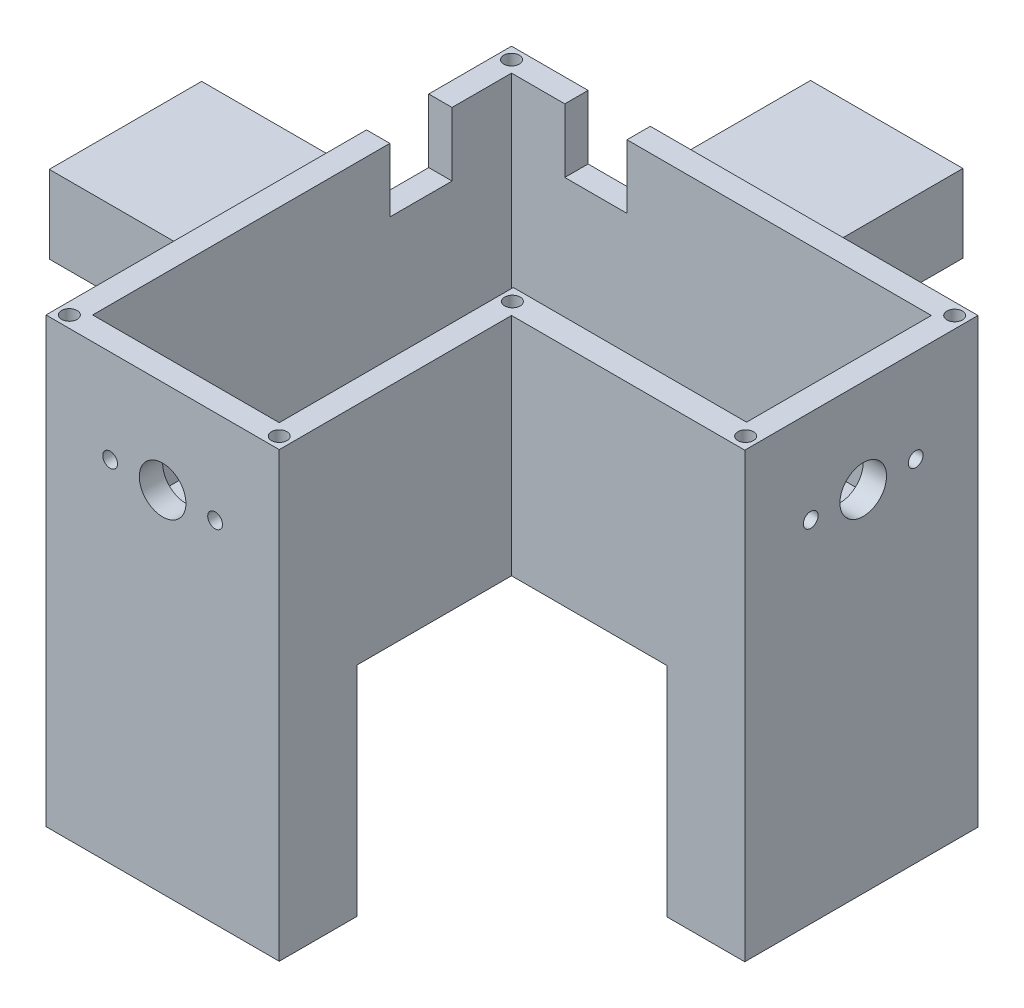
SolidWorks part; units mm, degrees
other "Marquage1"
sketch "Esquisse65" plane through (-83.92, 29, -58.86) normal (-0.3844, 0.8969, -0.2184) x (-0.4847, 0.0053, 0.8747)
ref_plane "Plan de face" through (0, 0, 0) normal (0, 0, 1) x (1, 0, 0)
ref_plane "Plan de dessus" through (0, 0, 0) normal (0, 1, 0) x (1, 0, 0)
ref_plane "Plan de droite" through (0, 0, 0) normal (1, 0, 0) x (0, 0, -1)
sketch "Esquisse1" plane through (0, 0, 0) normal (0, 1, 0) x (1, 0, 0)
  line L1 (0, 0) -> (-83.92, 0)
  line L2 (0, 0) -> (0, 19.6)
  line L3 (0, 19.6) -> (-83.92, 19.6)
  line L4 (-83.92, 0) -> (-83.92, 19.6)
  line L5 (-44.86, -24.34) -> (-25.26, -24.34)
  line L6 (-44.86, -24.34) -> (-44.86, 58.86)
  line L7 (-44.86, 58.86) -> (-25.26, 58.86)
  line L8 (-25.26, -24.34) -> (-25.26, 58.86)
  line L9 (-47.86, 22.6) -> (3, 22.6)
  line L10 (-47.86, 22.6) -> (-47.86, -27.34)
  line L11 (-47.86, -27.34) -> (3, -27.34)
  line L12 (3, 22.6) -> (3, -27.34)
  line L13 (3, -27.34) -> (-22.26, -27.34)
  line L14 (3, -27.34) -> (3, -3)
  line L15 (3, -3) -> (-22.26, -3)
  line L16 (-22.26, -27.34) -> (-22.26, -3)
  dimension "D1" = 83.92
  dimension "D2" = 19.6
  dimension "D3" = 19.6
  dimension "D4" = 83.2
  dimension "D5" = 39.26
  dimension "D6" = 3
  dimension "D7" = 3
  dimension "D8" = 25.26
  dimension "D9" = 3
  dimension "D10" = 3
  dimension "D11" = 3
  dimension "D12" = 3
extrude "Boss.-Extru.1" add sketch "Esquisse1" along normal blind 29.8 contours L10 L3 L4 L1 | L3 L10 L1 L6 | L9 L10 L3 L6 | L9 L6 L3 L8 | L11 L16 L15 L12 L9 L8 L3 L2 L1 L5 L6 L10 | L1 L8 L3 L6 | L5 L8 L1 L6 | L8 L1 L2 L3 | L6 L9 L8 L7
sketch "Esquisse2" plane through (0, 29.8, 0) normal (0, 1, 0) x (1, 0, 0)
  line L0 (-25.26, 22.6) -> (3, 22.6) construction
  line L1 (-44.86, 19.6) -> (-25.26, 19.6)
  line L2 (-44.86, 19.6) -> (-44.86, -24.34)
  line L3 (-44.86, -24.34) -> (-25.26, -24.34)
  line L4 (-25.26, 19.6) -> (-25.26, -24.34)
  line L5 (-25.26, 19.6) -> (0, 19.6)
  line L6 (-25.26, 19.6) -> (-25.26, 0)
  line L7 (-25.26, 0) -> (0, 0)
  line L8 (0, 19.6) -> (0, 0)
  line L11 (-47.86, -27.34) -> (-22.26, -27.34) construction
  line L12 (-22.26, -27.34) -> (-22.26, -3) construction
  line L13 (-47.86, 0) -> (-47.86, -27.34) construction
  dimension "D1" = 3
  dimension "D2" = 3
  dimension "D3" = 3
  dimension "D4" = 3
extrude "Enlèv. mat.-Extru.1" cut sketch "Esquisse2" against normal blind 24.8 contours L4 L1 L2 L3 | L8 L5 L4 L7
sketch "Esquisse3" plane through (0, 29.8, 0) normal (0, 1, 0) x (1, 0, 0)
  line L1 (-83.92, 19.6) -> (-47.86, 19.6)
  line L2 (-83.92, 19.6) -> (-83.92, 0)
  line L3 (-83.92, 0) -> (-47.86, 0)
  line L4 (-47.86, 19.6) -> (-47.86, 0)
  line L5 (-44.86, 58.86) -> (-25.26, 58.86)
  line L6 (-44.86, 58.86) -> (-44.86, 22.6)
  line L7 (-44.86, 22.6) -> (-25.26, 22.6)
  line L8 (-25.26, 58.86) -> (-25.26, 22.6)
extrude "Enlèv. mat.-Extru.2" cut sketch "Esquisse3" against normal blind 19.8
ref_plane "Plan1" through (-47.86, 29.8, 27.34) normal (0, -1, 0) x (-1, 0, 0)
sketch "Esquisse6" plane through (-47.86, 29.8, 27.34) normal (0, -1, 0) x (1, 0, 0)
  line L1 (0, -49.94) -> (56.5877, -49.94)
  line L2 (0, -49.94) -> (0, 5.1698)
  line L3 (0, 5.1698) -> (56.5877, 5.1698)
  line L4 (56.5877, -49.94) -> (56.5877, 5.1698)
extrude "Enlèv. mat.-Extru.5" cut sketch "Esquisse6" along normal blind 5
sketch "Esquisse7" plane through (-47.86, 0, 0) normal (-1, 0, 0) x (0, 0, 1)
  line L0 (-9.8, 10) -> (-9.8, 24.8)
  line L1 (0, 10) -> (-19.6, 10) construction
  line L2 (27.34, 24.8) -> (-22.6, 24.8) construction
  line L4 (-9.8, 24.8) -> (-13.8, 24.8)
  line L5 (-9.8, 24.8) -> (-9.8, 20.8)
  line L6 (-9.8, 20.8) -> (-13.8, 20.8)
  line L7 (-13.8, 24.8) -> (-13.8, 20.8)
  line L8 (-9.8, 20.8) -> (-5.8, 20.8)
  line L9 (-9.8, 20.8) -> (-9.8, 24.8)
  line L10 (-9.8, 24.8) -> (-5.8, 24.8)
  line L11 (-5.8, 20.8) -> (-5.8, 24.8)
  line M5 (27.34, 24.8) -> (-22.6, 24.8)
  dimension "D1" = 4
  dimension "D2" = 4
  dimension "D3" = 4
extrude "Enlèv. mat.-Extru.6" cut sketch "Esquisse7" against normal blind 5 contours L7 L6 L0 M5 | L8 L11 L0 M5
sketch "Esquisse8" plane through (0, 0, -22.6) normal (0, 0, -1) x (-1, 0, 0)
  line L0 (35.06, 10) -> (35.06, 24.8)
  line L1 (44.86, 10) -> (25.26, 10) construction
  line L2 (47.86, 24.8) -> (-3, 24.8) construction
  line L4 (35.06, 24.8) -> (31.06, 24.8)
  line L5 (35.06, 24.8) -> (35.06, 20.8)
  line L6 (35.06, 20.8) -> (31.06, 20.8)
  line L7 (31.06, 24.8) -> (31.06, 20.8)
  line L8 (35.06, 24.8) -> (39.06, 24.8)
  line L9 (35.06, 24.8) -> (35.06, 20.8)
  line L10 (35.06, 20.8) -> (39.06, 20.8)
  line L11 (39.06, 24.8) -> (39.06, 20.8)
  line M5 (47.86, 24.8) -> (-3, 24.8)
  dimension "D1" = 4
  dimension "D2" = 4
  dimension "D3" = 4
extrude "Enlèv. mat.-Extru.7" cut sketch "Esquisse8" against normal blind 5 contours L11 L0 L10 M5 | L7 L6 L0 M5
sketch "Esquisse10" plane through (-83.92, 0, 0) normal (-1, 0, 0) x (0, 0, 1)
  line L0 (-9.8, 0) -> (-9.8, 10)
  line L1 (0, 0) -> (-19.6, 0) construction
  line L2 (-19.6, 10) -> (0, 10) construction
  line L3 (-9.8, 10) -> (-19.6, 0)
  line L4 (-9.8, 10) -> (0, 0)
  circle A0 centre (-14.7, 5) radius 1.5
  circle A1 centre (-4.9, 5) radius 1.5
extrude "Enlèv. mat.-Extru.9" cut sketch "Esquisse10" against normal blind 5 contours L4 A1 | L4 A1 | L3 A0 | L3 A0
sketch "Esquisse11" plane through (0, 0, -58.86) normal (0, 0, -1) x (-1, 0, 0)
  line L0 (35.06, 0) -> (35.06, 10)
  line L1 (44.86, 0) -> (25.26, 0) construction
  line L2 (25.26, 10) -> (44.86, 10) construction
  line L3 (25.26, 10) -> (35.06, 0)
  line L4 (44.86, 10) -> (35.06, 0)
  circle A0 centre (30.16, 5) radius 1.5
  circle A1 centre (39.96, 5) radius 1.5
extrude "Enlèv. mat.-Extru.10" cut sketch "Esquisse11" against normal blind 5 contours L3 A0 | L3 A0 | L4 A1 | L4 A1
sketch "Esquisse20" plane through (0, 0, 0) normal (0, -1, 0) x (1, 0, 0)
  line L0 (-22.26, 27.34) -> (-22.26, 3) construction
  line L1 (-47.86, 27.34) -> (-22.26, 27.34)
  line L2 (-47.86, 27.34) -> (-47.86, 17.34)
  line L3 (-47.86, 17.34) -> (-22.26, 17.34)
  line L4 (-22.26, 27.34) -> (-22.26, 17.34)
extrude "Boss.-Extru.4" add sketch "Esquisse20" along normal blind 30.13
sketch "Esquisse21" plane through (0, 0, 0) normal (0, -1, 0) x (1, 0, 0)
  line L0 (-25.26, -22.6) -> (3, -22.6) construction
  line L1 (3, 3) -> (-7, 3)
  line L2 (3, 3) -> (3, -22.6)
  line L3 (3, -22.6) -> (-7, -22.6)
  line L4 (-7, 3) -> (-7, -22.6)
  dimension "D1" = 10
extrude "Boss.-Extru.5" add sketch "Esquisse21" along normal blind 30.13
sketch "Esquisse22" plane through (0, -30.13, 0) normal (0, -1, 0) x (1, 0, 0)
  line L0 (-35.06, 17.34) -> (-35.06, 27.34)
  line L1 (-47.86, 17.34) -> (-22.26, 17.34) construction
  line L2 (-22.26, 27.34) -> (-47.86, 27.34) construction
  line L3 (-35.06, 27.34) -> (-47.86, 17.34)
  line L4 (-35.06, 27.34) -> (-22.26, 17.34)
  line L5 (-7, -9.8) -> (3, -9.8)
  line L6 (-7, 3) -> (-7, -22.6) construction
  line L7 (3, -22.6) -> (3, 3) construction
  line L8 (3, -9.8) -> (-7, -22.6)
  line L9 (3, -9.8) -> (-7, 3)
  circle A0 centre (-28.66, 22.34) radius 1.5
  circle A1 centre (-41.46, 22.34) radius 1.5
  circle A2 centre (-2, -16.2) radius 1.5
  circle A3 centre (-2, -3.4) radius 1.5
extrude "Enlèv. mat.-Extru.17" cut sketch "Esquisse22" against normal blind 5 contours L9 A3 | L4 A0 | L4 A0 | L3 A1 | L3 A1 | A2
sketch "Esquisse23" plane through (0, 0, -22.6) normal (0, 0, -1) x (-1, 0, 0)
  line L0 (44.86, 10) -> (25.26, 10) construction
  line L1 (-3, 24.8) -> (7, 24.8)
  line L2 (-3, 24.8) -> (-3, -30.13)
  line L3 (-3, -30.13) -> (7, -30.13)
  line L4 (7, 24.8) -> (7, -30.13)
  line L5 (25.26, 0) -> (7, 0)
  line L6 (25.26, 0) -> (25.26, 24.8)
  line L7 (25.26, 24.8) -> (7, 24.8)
  line L8 (7, 0) -> (7, 24.8)
  line L9 (47.86, 0) -> (44.86, 0)
  line L10 (47.86, 0) -> (47.86, 10)
  line L11 (47.86, 10) -> (44.86, 10)
  line L12 (44.86, 0) -> (44.86, 10)
  line L13 (47.86, 24.8) -> (39.06, 24.8)
  line L14 (47.86, 24.8) -> (47.86, 10)
  line L15 (47.86, 10) -> (39.06, 10)
  line L16 (39.06, 24.8) -> (39.06, 10)
  line L18 (39.06, 10) -> (31.06, 10)
  line L19 (39.06, 10) -> (39.06, 20.8)
  line L20 (39.06, 20.8) -> (31.06, 20.8)
  line L21 (31.06, 10) -> (31.06, 20.8)
  line L22 (31.06, 24.8) -> (25.26, 24.8)
  line L23 (31.06, 24.8) -> (31.06, 10)
  line L24 (31.06, 10) -> (25.26, 10)
  line L25 (25.26, 24.8) -> (25.26, 10)
  line M26 (47.86, 24.8) -> (39.06, 24.8)
  line M27 (39.06, 24.8) -> (39.06, 20.8)
  line M28 (39.06, 20.8) -> (31.06, 20.8)
  line M29 (31.06, 20.8) -> (31.06, 24.8)
  line M30 (31.06, 24.8) -> (-3, 24.8)
  line M31 (-3, 24.8) -> (-3, -30.13)
  line M32 (-3, -30.13) -> (7, -30.13)
  line M33 (7, -30.13) -> (7, 0)
  line M34 (7, 0) -> (25.26, 0)
  line M35 (25.26, 0) -> (25.26, 10)
  line M36 (25.26, 10) -> (44.86, 10)
  line M39 (47.86, 0) -> (47.86, 24.8)
extrude "Boss.-Extru.9" add sketch "Esquisse23" along normal blind 2.2 contours L16 L11 M27 M36 M39 M26 | L21 L16 M36 M28 | L6 L4 M35 M30 M34 | L21 L6 M36 M29 M30 | L4 M30 M31 M32 M33
sketch "Esquisse28" plane through (0, 0, 3) normal (0, 0, 1) x (1, 0, 0)
  line L0 (3, 24.8) -> (3, -30.13) construction
  line L1 (-22.26, 24.8) -> (3, 24.8)
  line L2 (-22.26, 24.8) -> (-22.26, 0)
  line L3 (-22.26, 0) -> (3, 0)
  line L4 (3, 24.8) -> (3, 0)
  line L6 (3, 0) -> (-7, 0)
  line L7 (3, 0) -> (3, -30.13)
  line L8 (3, -30.13) -> (-7, -30.13)
  line L9 (-7, 0) -> (-7, -30.13)
  line M1 (3, -30.13) -> (3, 24.8)
  line M2 (3, 24.8) -> (-22.26, 24.8)
  line M3 (-22.26, 24.8) -> (-22.26, 0)
  line M4 (-22.26, 0) -> (-7, 0)
  line M5 (-7, 0) -> (-7, -30.13)
  line M6 (-7, -30.13) -> (3, -30.13)
extrude "Boss.-Extru.10" add sketch "Esquisse28" along normal blind 2.2 contours L3 M4 M1 M2 M3 | L3 M5 M6 M1
sketch "Esquisse29" plane through (-22.26, 0, 0) normal (1, 0, 0) x (0, 0, -1)
  line L1 (-27.34, 24.8) -> (-5.2, 24.8)
  line L2 (-27.34, 24.8) -> (-27.34, 0)
  line L3 (-27.34, 0) -> (-5.2, 0)
  line L4 (-5.2, 24.8) -> (-5.2, 0)
  line L5 (-17.34, 0) -> (-27.34, 0)
  line L6 (-17.34, 0) -> (-17.34, -30.13)
  line L7 (-17.34, -30.13) -> (-27.34, -30.13)
  line L8 (-27.34, 0) -> (-27.34, -30.13)
  line M1 (-17.34, 0) -> (-5.2, 0)
  line M2 (-5.2, 0) -> (-5.2, 24.8)
  line M3 (-5.2, 24.8) -> (-27.34, 24.8)
  line M4 (-27.34, 24.8) -> (-27.34, -30.13)
  line M5 (-27.34, -30.13) -> (-17.34, -30.13)
  line M6 (-17.34, -30.13) -> (-17.34, 0)
extrude "Boss.-Extru.11" add sketch "Esquisse29" along normal blind 2.2 contours L3 M4 M1 M2 M3 | L3 M4 M5 M6
sketch "Esquisse30" plane through (-47.86, 0, 0) normal (-1, 0, 0) x (0, 0, 1)
  line L0 (-13.8, 24.8) -> (-13.8, 20.8) construction
  line L1 (-24.8, 10) -> (-13.8, 10)
  line L2 (-24.8, 10) -> (-24.8, 24.8)
  line L3 (-24.8, 24.8) -> (-13.8, 24.8)
  line L4 (-13.8, 10) -> (-13.8, 24.8)
  line L5 (-13.8, 24.8) -> (-24.8, 24.8) construction
  line L6 (27.34, 24.8) -> (27.34, -30.13) construction
  line L7 (-22.6, 0) -> (-19.6, 0)
  line L8 (-22.6, 0) -> (-22.6, 10)
  line L9 (-22.6, 10) -> (-19.6, 10)
  line L10 (-19.6, 0) -> (-19.6, 10)
  line L11 (-13.8, 10) -> (-5.8, 10)
  line L12 (-13.8, 10) -> (-13.8, 20.8)
  line L13 (-13.8, 20.8) -> (-5.8, 20.8)
  line L14 (-5.8, 10) -> (-5.8, 20.8)
  line L15 (-5.8, 24.8) -> (27.34, 24.8)
  line L16 (-5.8, 24.8) -> (-5.8, 10)
  line L17 (-5.8, 10) -> (27.34, 10)
  line L18 (27.34, 24.8) -> (27.34, 10)
  line L20 (27.34, 10) -> (0, 10)
  line L21 (27.34, 10) -> (27.34, 0)
  line L22 (27.34, 0) -> (0, 0)
  line L23 (0, 10) -> (0, 0)
  line L24 (27.34, 0) -> (17.34, 0)
  line L25 (27.34, 0) -> (27.34, -30.13)
  line L26 (27.34, -30.13) -> (17.34, -30.13)
  line L27 (17.34, 0) -> (17.34, -30.13)
  line M5 (27.34, 24.8) -> (-5.8, 24.8)
  line M6 (-5.8, 24.8) -> (-5.8, 20.8)
  line M7 (-5.8, 20.8) -> (-13.8, 20.8)
  line M8 (-13.8, 20.8) -> (-13.8, 24.8)
  line M9 (-13.8, 24.8) -> (-24.8, 24.8)
  line M10 (-24.8, 24.8) -> (-24.8, 10)
  line M11 (-24.8, 10) -> (-22.6, 10)
  line M12 (-22.6, 10) -> (-22.6, 0)
  line M13 (-22.6, 0) -> (-19.6, 0)
  line M14 (-19.6, 0) -> (-19.6, 10)
  line M15 (-19.6, 10) -> (0, 10)
  line M16 (0, 10) -> (0, 0)
  line M17 (0, 0) -> (17.34, 0)
  line M18 (17.34, 0) -> (17.34, -30.13)
  line M19 (17.34, -30.13) -> (27.34, -30.13)
  line M20 (27.34, -30.13) -> (27.34, 24.8)
extrude "Boss.-Extru.12" add sketch "Esquisse30" along normal blind 2.2 contours L1 M12 M13 M14 | L4 L1 M15 M8 M9 M10 M11 | L14 L4 M15 M7 | L17 L14 M15 M20 M5 M6 | L22 L17 M20 M16 M17 | L22 M20 M18 M19
sketch "Esquisse31" plane through (-25.26, 0, 0) normal (-1, 0, 0) x (0, 0, 1)
  line L1 (0, 5) -> (24.34, 5)
  line L2 (0, 5) -> (0, 24.8)
  line L3 (0, 24.8) -> (24.34, 24.8)
  line L4 (24.34, 5) -> (24.34, 24.8)
extrude "Enlèv. mat.-Extru.18" cut sketch "Esquisse31" against normal blind 2.2
sketch "Esquisse32" plane through (0, 0, 0) normal (0, 0, -1) x (-1, 0, 0)
  line L1 (23.06, 5) -> (0, 5)
  line L2 (23.06, 5) -> (23.06, 24.8)
  line L3 (23.06, 24.8) -> (0, 24.8)
  line L4 (0, 5) -> (0, 24.8)
extrude "Enlèv. mat.-Extru.19" cut sketch "Esquisse32" against normal blind 2.2
sketch "Esquisse33" plane through (0, 0, -19.6) normal (0, 0, 1) x (1, 0, 0)
  line L1 (-44.86, 5) -> (0, 5)
  line L2 (-44.86, 5) -> (-44.86, 24.8)
  line L3 (-44.86, 24.8) -> (0, 24.8)
  line L4 (0, 5) -> (0, 24.8)
extrude "Enlèv. mat.-Extru.20" cut sketch "Esquisse33" against normal blind 2.2
sketch "Esquisse34" plane through (-44.86, 0, 0) normal (1, 0, 0) x (0, 0, -1)
  line L1 (-24.34, 5) -> (21.8, 5)
  line L2 (-24.34, 5) -> (-24.34, 24.8)
  line L3 (-24.34, 24.8) -> (21.8, 24.8)
  line L4 (21.8, 5) -> (21.8, 24.8)
extrude "Enlèv. mat.-Extru.21" cut sketch "Esquisse34" against normal blind 2.2
sketch "Esquisse36" plane through (0, 0, 27.34) normal (0, 0, 1) x (1, 0, 0)
  line L1 (-50.06, -30.13) -> (-20.06, -30.13)
  line L2 (-50.06, -30.13) -> (-50.06, 24.8)
  line L3 (-50.06, 24.8) -> (-20.06, 24.8)
  line L4 (-20.06, -30.13) -> (-20.06, 24.8)
extrude "Boss.-Extru.13" add sketch "Esquisse36" along normal blind 8.09
sketch "Esquisse37" plane through (3, 0, 0) normal (1, 0, 0) x (0, 0, -1)
  line L1 (-5.2, -30.13) -> (24.8, -30.13)
  line L2 (-5.2, -30.13) -> (-5.2, 24.8)
  line L3 (-5.2, 24.8) -> (24.8, 24.8)
  line L4 (24.8, -30.13) -> (24.8, 24.8)
extrude "Boss.-Extru.14" add sketch "Esquisse37" along normal blind 8.09
sketch "Esquisse38" plane through (0, 0, 24.34) normal (0, 0, -1) x (-1, 0, 0)
  line L1 (23.06, 5) -> (47.06, 5)
  line L2 (23.06, 5) -> (23.06, 24.8)
  line L3 (23.06, 24.8) -> (47.06, 24.8)
  line L4 (47.06, 5) -> (47.06, 24.8)
extrude "Enlèv. mat.-Extru.24" cut sketch "Esquisse38" against normal blind 8.09
sketch "Esquisse39" plane through (0, 0, 0) normal (-1, 0, 0) x (0, 0, 1)
  line L1 (-21.8, 5) -> (2.2, 5)
  line L2 (-21.8, 5) -> (-21.8, 24.8)
  line L3 (-21.8, 24.8) -> (2.2, 24.8)
  line L4 (2.2, 5) -> (2.2, 24.8)
extrude "Enlèv. mat.-Extru.25" cut sketch "Esquisse39" against normal blind 8.09
sketch "Esquisse40" plane through (-7, 0, 0) normal (-1, 0, 0) x (0, 0, 1)
  line L1 (-24.8, 0) -> (5.2, 0)
  line L2 (-24.8, 0) -> (-24.8, -30.13)
  line L3 (-24.8, -30.13) -> (5.2, -30.13)
  line L4 (5.2, 0) -> (5.2, -30.13)
extrude "Enlèv. mat.-Extru.26" cut sketch "Esquisse40" against normal blind 8.09
sketch "Esquisse41" plane through (0, 0, 17.34) normal (0, 0, -1) x (-1, 0, 0)
  line L1 (20.06, -30.13) -> (50.06, -30.13)
  line L2 (20.06, -30.13) -> (20.06, 0)
  line L3 (20.06, 0) -> (50.06, 0)
  line L4 (50.06, -30.13) -> (50.06, 0)
extrude "Enlèv. mat.-Extru.27" cut sketch "Esquisse41" against normal blind 8.09
sketch "Esquisse42" plane through (0, 0, -22.6) normal (0, 0, -1) x (-1, 0, 0)
  line L1 (50.06, 0) -> (44.86, 0)
  line L2 (50.06, 0) -> (50.06, 10)
  line L3 (50.06, 10) -> (44.86, 10)
  line L4 (44.86, 0) -> (44.86, 10)
extrude "Boss.-Extru.15" add sketch "Esquisse42" along normal blind 2.2
sketch "Esquisse43" plane through (0, 24.8, 0) normal (0, 1, 0) x (1, 0, 0)
  line L0 (11.09, -5.2) -> (-20.06, -5.2) construction
  line L1 (-31.06, 24.8) -> (8.09, 24.8)
  line L2 (-31.06, 24.8) -> (-31.06, 21.8)
  line L3 (-31.06, 21.8) -> (8.09, 21.8)
  line L4 (8.09, 24.8) -> (8.09, 21.8)
  line L5 (11.09, 24.8) -> (8.09, 24.8)
  line L6 (11.09, 24.8) -> (11.09, -5.2)
  line L7 (11.09, -5.2) -> (8.09, -5.2)
  line L8 (8.09, 24.8) -> (8.09, -5.2)
  line L9 (-23.06, -2.2) -> (8.09, -2.2) construction
  line L10 (8.09, -5.2) -> (-22.9918, -5.2)
  line L11 (8.09, -5.2) -> (8.09, -2.2)
  line L12 (8.09, -2.2) -> (-22.9918, -2.2)
  line L13 (-22.9918, -5.2) -> (-22.9918, -2.2)
  line L14 (-20.06, -35.43) -> (-50.06, -35.43) construction
  line L15 (-20.06, -5.2) -> (-22.9918, -5.2)
  line L16 (-20.06, -5.2) -> (-20.06, -35.43)
  line L17 (-20.06, -35.43) -> (-22.9918, -35.43)
  line L18 (-22.9918, -5.2) -> (-22.9918, -35.43)
  line L19 (-50.06, -35.43) -> (-50.06, 5.8) construction
  line L20 (-22.9918, -35.43) -> (-50.06, -35.43)
  line L21 (-22.9918, -35.43) -> (-22.9918, -32.4915)
  line L22 (-22.9918, -32.4915) -> (-50.06, -32.4915)
  line L23 (-50.06, -35.43) -> (-50.06, -32.4915)
  line L24 (-47.06, 5.8) -> (-50.06, 5.8) construction
  line L25 (-47.06, -32.43) -> (-50.06, -32.43)
  line L26 (-47.06, -32.43) -> (-47.06, 5.8)
  line L27 (-47.06, 5.8) -> (-50.06, 5.8)
  line L28 (-50.06, -32.43) -> (-50.06, 5.8)
  line L29 (-47.06, 21.8) -> (-47.06, 13.8) construction
  line L30 (-47.06, 13.8) -> (-50.06, 13.8)
  line L31 (-47.06, 13.8) -> (-47.06, 24.8)
  line L32 (-47.06, 24.8) -> (-50.06, 24.8)
  line L33 (-50.06, 13.8) -> (-50.06, 24.8)
  line L35 (-47.06, 24.8) -> (-39.06, 24.8)
  line L36 (-47.06, 24.8) -> (-47.06, 21.8)
  line L37 (-47.06, 21.8) -> (-39.06, 21.8)
  line L38 (-39.06, 24.8) -> (-39.06, 21.8)
  line M1 (-31.06, 21.8) -> (8.09, 21.8)
  line M2 (8.09, 21.8) -> (8.09, -2.2)
  line M3 (8.09, -2.2) -> (-23.06, -2.2)
  line M6 (-47.06, -32.43) -> (-47.06, 5.8)
  line M7 (-47.06, 5.8) -> (-50.06, 5.8)
  line M8 (-50.06, 5.8) -> (-50.06, -35.43)
  line M9 (-50.06, -35.43) -> (-20.06, -35.43)
  line M10 (-20.06, -35.43) -> (-20.06, -5.2)
  line M11 (-20.06, -5.2) -> (11.09, -5.2)
  line M12 (11.09, -5.2) -> (11.09, 24.8)
  line M13 (11.09, 24.8) -> (-31.06, 24.8)
  line M14 (-31.06, 24.8) -> (-31.06, 21.8)
extrude "Boss.-Extru.16" add sketch "Esquisse43" along normal blind 4.2 contours L33 L30 L31 L32 | L38 L35 L31 L37 | L4 M13 M14 M1 | L8 L4 M2 M11 M12 M13 | L13 L10 L8 M11 M3 | L10 L18 M9 M10 | L18 L22 M8 M9 | L25 M6 M7 M8
sketch "Esquisse46" plane through (-50.06, 0, 0) normal (-1, 0, 0) x (0, 0, 1)
  line L1 (0.9119, 11.9236) -> (-19.8928, 11.9236)
  line L2 (0.9119, 11.9236) -> (0.9119, 20.434)
  line L3 (0.9119, 20.434) -> (-19.8928, 20.434)
  line L4 (-19.8928, 11.9236) -> (-19.8928, 20.434)
extrude "Boss.-Extru.17" add sketch "Esquisse46" against normal blind 3
sketch "Esquisse47" plane through (0, 24.8, 0) normal (0, 1, 0) x (1, 0, 0)
  line L1 (-50.06, -32.43) -> (-22.9918, -32.43)
  line L2 (-50.06, -32.43) -> (-50.06, -32.4915)
  line L3 (-50.06, -32.4915) -> (-22.9918, -32.4915)
  line L4 (-22.9918, -32.43) -> (-22.9918, -32.4915)
  line L5 (-22.9918, -32.43) -> (-23.06, -32.43)
  line L6 (-22.9918, -32.43) -> (-22.9918, -2.2)
  line L7 (-22.9918, -2.2) -> (-23.06, -2.2)
  line L8 (-23.06, -32.43) -> (-23.06, -2.2)
  line M1 (-47.06, -32.43) -> (-50.06, -32.43)
  line M2 (-50.06, -32.43) -> (-50.06, -32.4915)
  line M3 (-50.06, -32.4915) -> (-22.9918, -32.4915)
  line M4 (-22.9918, -32.4915) -> (-22.9918, -2.2)
  line M5 (-22.9918, -2.2) -> (-23.06, -2.2)
  line M6 (-23.06, -2.2) -> (-23.06, -32.43)
  line M7 (-23.06, -32.43) -> (-47.06, -32.43)
extrude "Boss.-Extru.18" add sketch "Esquisse47" along normal blind 4.2 contours L1 M6 M4 M5 | L1 M7 M1 M2 M3 M4
sketch "Esquisse49" plane through (0, -30.13, 0) normal (0, -1, 0) x (1, 0, 0)
  line L1 (-50.06, 35.43) -> (14.5602, 35.43)
  line L2 (-50.06, 35.43) -> (-50.06, -45.084)
  line L3 (-50.06, -45.084) -> (14.5602, -45.084)
  line L4 (14.5602, 35.43) -> (14.5602, -45.084)
extrude "Enlèv. mat.-Extru.30" cut sketch "Esquisse49" against normal blind 2.13
sketch "Esquisse50" plane through (-20.06, 0, 0) normal (1, 0, 0) x (0, 0, -1)
  line L1 (-35.43, 29) -> (-5.2, 29)
  line L2 (-35.43, 29) -> (-35.43, 0)
  line L3 (-35.43, 0) -> (-5.2, 0)
  line L4 (-5.2, 29) -> (-5.2, 0)
  line L5 (-35.43, 0) -> (-25.43, 0)
  line L6 (-35.43, 0) -> (-35.43, -28)
  line L7 (-35.43, -28) -> (-25.43, -28)
  line L8 (-25.43, 0) -> (-25.43, -28)
  line M1 (-35.43, 29) -> (-35.43, -28)
  line M2 (-35.43, -28) -> (-25.43, -28)
  line M3 (-25.43, -28) -> (-25.43, 0)
  line M4 (-25.43, 0) -> (-5.2, 0)
  line M5 (-5.2, 0) -> (-5.2, 29)
  line M6 (-5.2, 29) -> (-35.43, 29)
extrude "Boss.-Extru.19" add sketch "Esquisse50" along normal blind 1.15 contours L3 M1 M4 M5 M6 | L3 M1 M2 M3
sketch "Esquisse51" plane through (-23.06, 0, 0) normal (-1, 0, 0) x (0, 0, 1)
  line L0 (2.2, 5) -> (32.43, 5) construction
  line L1 (2.2, 29) -> (32.43, 29)
  line L2 (2.2, 29) -> (2.2, 5)
  line L3 (2.2, 5) -> (32.43, 5)
  line L4 (32.43, 29) -> (32.43, 5)
extrude "Enlèv. mat.-Extru.31" cut sketch "Esquisse51" against normal blind 1.15
sketch "Esquisse52" plane through (-47.06, 0, 0) normal (1, 0, 0) x (0, 0, -1)
  line L1 (-32.43, 29) -> (5.8, 29)
  line L2 (-32.43, 29) -> (-32.43, 20.8)
  line L3 (-32.43, 20.8) -> (5.8, 20.8)
  line L4 (5.8, 29) -> (5.8, 20.8)
  line L5 (13.8, 29) -> (21.8, 29)
  line L6 (13.8, 29) -> (13.8, 5)
  line L7 (13.8, 5) -> (21.8, 5)
  line L8 (21.8, 29) -> (21.8, 5)
  line L9 (13.8, 5) -> (-32.43, 5)
  line L10 (13.8, 5) -> (13.8, 20.8)
  line L11 (13.8, 20.8) -> (-32.43, 20.8)
  line L12 (-32.43, 5) -> (-32.43, 20.8)
  line M1 (5.8, 20.8) -> (5.8, 29)
  line M2 (5.8, 29) -> (-32.43, 29)
  line M3 (-32.43, 29) -> (-32.43, 5)
  line M4 (-32.43, 5) -> (21.8, 5)
  line M5 (21.8, 5) -> (21.8, 29)
  line M6 (21.8, 29) -> (13.8, 29)
  line M7 (13.8, 29) -> (13.8, 20.8)
  line M8 (13.8, 20.8) -> (5.8, 20.8)
extrude "Boss.-Extru.20" add sketch "Esquisse52" along normal blind 1.15 contours L3 M3 M1 M2 | L6 L3 M8 M3 M4 | L6 M7 M4 M5 M6
sketch "Esquisse53" plane through (-50.06, 0, 0) normal (-1, 0, 0) x (0, 0, 1)
  line L0 (-24.8, 29) -> (-24.8, 0) construction
  line L1 (-19.6, 0) -> (-24.8, 0)
  line L2 (-19.6, 0) -> (-19.6, 29)
  line L3 (-19.6, 29) -> (-24.8, 29)
  line L4 (-24.8, 0) -> (-24.8, 29)
  line L5 (35.43, 29) -> (35.43, -28) construction
  line L6 (-19.6, 29) -> (-13.8, 29)
  line L7 (-19.6, 29) -> (-19.6, 20.8)
  line L8 (-19.6, 20.8) -> (-13.8, 20.8)
  line L9 (-13.8, 29) -> (-13.8, 20.8)
  line L10 (-19.6, 10) -> (35.43, 10)
  line L11 (-19.6, 10) -> (-19.6, 20.8)
  line L12 (-19.6, 20.8) -> (35.43, 20.8)
  line L13 (35.43, 10) -> (35.43, 20.8)
  line L14 (25.43, -28) -> (25.43, 0) construction
  line L15 (35.43, 20.8) -> (-5.8, 20.8)
  line L16 (35.43, 20.8) -> (35.43, 29)
  line L17 (35.43, 29) -> (-5.8, 29)
  line L18 (-5.8, 20.8) -> (-5.8, 29)
  line L19 (35.43, 10) -> (0, 10)
  line L20 (35.43, 10) -> (35.43, 0)
  line L21 (35.43, 0) -> (0, 0)
  line L22 (0, 10) -> (0, 0)
  line L23 (35.43, 0) -> (25.43, 0)
  line L24 (35.43, 0) -> (35.43, -28)
  line L25 (35.43, -28) -> (25.43, -28)
  line L26 (25.43, 0) -> (25.43, -28)
  line M1 (25.43, 0) -> (25.43, -28)
  line M2 (25.43, -28) -> (35.43, -28)
  line M3 (35.43, -28) -> (35.43, 29)
  line M4 (35.43, 29) -> (-5.8, 29)
  line M5 (-5.8, 29) -> (-5.8, 20.8)
  line M6 (-5.8, 20.8) -> (-13.8, 20.8)
  line M7 (-13.8, 20.8) -> (-13.8, 29)
  line M8 (-13.8, 29) -> (-24.8, 29)
  line M9 (-24.8, 29) -> (-24.8, 0)
  line M10 (-24.8, 0) -> (-19.6, 0)
  line M11 (-19.6, 0) -> (-19.6, 10)
  line M12 (-19.6, 10) -> (0, 10)
  line M13 (0, 10) -> (0, 0)
  line M14 (0, 0) -> (25.43, 0)
extrude "Enlèv. mat.-Extru.32" cut sketch "Esquisse53" against normal blind 1.15 contours L2 M11 M8 M9 M10 | L2 L8 M7 M8 | L12 L8 L2 L10 M6 M12 M3 | L12 M5 M3 M4 | L21 L10 M3 M13 M14 | L21 M3 M1 M2
sketch "Esquisse54" plane through (0, 0, 5.2) normal (0, 0, 1) x (1, 0, 0)
  line L0 (11.09, 29) -> (11.09, -28) construction
  line L1 (-18.91, 29) -> (11.09, 29)
  line L2 (-18.91, 29) -> (-18.91, 0)
  line L3 (-18.91, 0) -> (11.09, 0)
  line L4 (11.09, 29) -> (11.09, 0)
  line L6 (11.09, 0) -> (1.09, 0)
  line L7 (11.09, 0) -> (11.09, -28)
  line L8 (11.09, -28) -> (1.09, -28)
  line L9 (1.09, 0) -> (1.09, -28)
  line M1 (-18.91, 29) -> (-18.91, 0)
  line M2 (-18.91, 0) -> (1.09, 0)
  line M3 (1.09, 0) -> (1.09, -28)
  line M4 (1.09, -28) -> (11.09, -28)
  line M5 (11.09, -28) -> (11.09, 29)
  line M6 (11.09, 29) -> (-18.91, 29)
extrude "Boss.-Extru.21" add sketch "Esquisse54" along normal blind 0.23 contours L3 M2 M5 M6 M1 | L3 M3 M4 M5
sketch "Esquisse55" plane through (0, 0, -21.8) normal (0, 0, 1) x (1, 0, 0)
  line L0 (8.09, 29) -> (8.09, 5) construction
  line L1 (-45.91, 5) -> (-39.06, 5)
  line L2 (-45.91, 5) -> (-45.91, 29)
  line L3 (-45.91, 29) -> (-39.06, 29)
  line L4 (-39.06, 5) -> (-39.06, 29)
  line L5 (-39.06, 20.8) -> (8.09, 20.8)
  line L6 (-39.06, 20.8) -> (-39.06, 5)
  line L7 (-39.06, 5) -> (8.09, 5)
  line L8 (8.09, 20.8) -> (8.09, 5)
  line L9 (-45.91, 5) -> (8.09, 5) construction
  line L11 (-31.06, 29) -> (8.09, 29)
  line L12 (-31.06, 29) -> (-31.06, 20.8)
  line L13 (-31.06, 20.8) -> (8.09, 20.8)
  line L14 (8.09, 29) -> (8.09, 20.8)
  line M1 (-39.06, 29) -> (-45.91, 29)
  line M2 (-45.91, 29) -> (-45.91, 5)
  line M3 (-45.91, 5) -> (8.09, 5)
  line M4 (8.09, 5) -> (8.09, 29)
  line M5 (8.09, 29) -> (-31.06, 29)
  line M6 (-31.06, 29) -> (-31.06, 20.8)
  line M7 (-31.06, 20.8) -> (-39.06, 20.8)
  line M8 (-39.06, 20.8) -> (-39.06, 29)
extrude "Boss.-Extru.22" add sketch "Esquisse55" along normal blind 0.23 contours L4 M3 M8 M1 M2 | L5 L4 M7 M3 M4 | L5 M6 M4 M5
sketch "Esquisse56" plane through (0, 0, -24.8) normal (0, 0, -1) x (-1, 0, 0)
  line L0 (48.91, 29) -> (48.91, 0) construction
  line L1 (-1.09, -28) -> (-11.09, -28)
  line L2 (-1.09, -28) -> (-1.09, 29)
  line L3 (-1.09, 29) -> (-11.09, 29)
  line L4 (-11.09, -28) -> (-11.09, 29)
  line L5 (-1.09, 0) -> (25.26, 0)
  line L6 (-1.09, 0) -> (-1.09, 10)
  line L7 (-1.09, 10) -> (25.26, 10)
  line L8 (25.26, 0) -> (25.26, 10)
  line L9 (25.26, 10) -> (-1.09, 10)
  line L10 (25.26, 10) -> (25.26, 29)
  line L11 (25.26, 29) -> (-1.09, 29)
  line L12 (-1.09, 10) -> (-1.09, 29)
  line L13 (25.26, 29) -> (31.06, 29)
  line L14 (25.26, 29) -> (25.26, 20.8)
  line L15 (25.26, 20.8) -> (31.06, 20.8)
  line L16 (31.06, 29) -> (31.06, 20.8)
  line L17 (25.26, 10) -> (48.91, 10)
  line L18 (25.26, 10) -> (25.26, 20.8)
  line L19 (25.26, 20.8) -> (48.91, 20.8)
  line L20 (48.91, 10) -> (48.91, 20.8)
  line L22 (39.06, 29) -> (48.91, 29)
  line L23 (39.06, 29) -> (39.06, 20.8)
  line L24 (39.06, 20.8) -> (48.91, 20.8)
  line L25 (48.91, 29) -> (48.91, 20.8)
  line L26 (48.91, 0) -> (44.86, 0)
  line L27 (48.91, 0) -> (48.91, 10)
  line L28 (48.91, 10) -> (44.86, 10)
  line L29 (44.86, 0) -> (44.86, 10)
  line M1 (44.86, 0) -> (48.91, 0)
  line M2 (48.91, 0) -> (48.91, 29)
  line M3 (48.91, 29) -> (39.06, 29)
  line M4 (39.06, 29) -> (39.06, 20.8)
  line M5 (39.06, 20.8) -> (31.06, 20.8)
  line M6 (31.06, 20.8) -> (31.06, 29)
  line M7 (31.06, 29) -> (-11.09, 29)
  line M8 (-11.09, 29) -> (-11.09, -28)
  line M9 (-11.09, -28) -> (-1.09, -28)
  line M10 (-1.09, -28) -> (-1.09, 0)
  line M11 (-1.09, 0) -> (25.26, 0)
  line M12 (25.26, 0) -> (25.26, 10)
  line M13 (25.26, 10) -> (44.86, 10)
  line M14 (44.86, 10) -> (44.86, 0)
extrude "Enlèv. mat.-Extru.33" cut sketch "Esquisse56" against normal blind 0.23 contours L2 M10 M7 M8 M9 | L7 L2 M11 M12 | L7 L10 L2 M7 | L19 L15 L10 L17 M5 M13 M2 | L10 L15 M6 M7 | L19 M4 M2 M3 | L17 M14 M1 M2
sketch "Esquisse57" plane through (8.09, 0, 0) normal (-1, 0, 0) x (0, 0, 1)
  line L0 (-21.57, 29) -> (2.2, 5)
  line L1 (-16.435, 17) -> (-2.935, 17)
  circle A0 centre (-9.685, 17) radius 3
  circle A1 centre (-9.685, 17) radius 6.75
  circle A2 centre (-16.435, 17) radius 0.95
  circle A3 centre (-2.935, 17) radius 0.95
extrude "Enlèv. mat.-Extru.34" cut sketch "Esquisse57" against normal blind 7.23 contours A1 A2 | A1 A2 L1 | L1 A2 A1 | L0 A0 L1 | L1 A0 L0 | L1 A0 L0 | L0 A0 L1 | L1 A3 A1 | A1 A3 L1 | A1 A3
sketch "Esquisse58" plane through (0, 0, 32.43) normal (0, 0, -1) x (-1, 0, 0)
  line L0 (21.91, 29) -> (45.91, 5)
  line L1 (27.16, 17) -> (40.66, 17)
  circle A0 centre (33.91, 17) radius 3
  circle A1 centre (33.91, 17) radius 6.75
  circle A2 centre (27.16, 17) radius 0.95
  circle A3 centre (40.66, 17) radius 0.95
extrude "Enlèv. mat.-Extru.35" cut sketch "Esquisse58" against normal blind 7.23 contours A1 A2 | L1 A2 A1 | A1 A2 L1 | L1 A0 L0 | L0 A0 L1 | L1 A0 L0 | L0 A0 L1 | A1 A3 | A1 A3 L1 | L1 A3 A1
sketch "Esquisse59" plane through (0, 0, 5.43) normal (0, 0, 1) x (1, 0, 0)
  line L0 (11.09, -28) -> (11.09, 29) construction
  line L1 (-18.91, 29) -> (11.09, 29)
  line L2 (-18.91, 29) -> (-18.91, 0)
  line L3 (-18.91, 0) -> (11.09, 0)
  line L4 (11.09, 29) -> (11.09, 0)
  line L6 (11.09, 0) -> (1.09, 0)
  line L7 (11.09, 0) -> (11.09, -28)
  line L8 (11.09, -28) -> (1.09, -28)
  line L9 (1.09, 0) -> (1.09, -28)
  line M1 (-18.91, 0) -> (1.09, 0)
  line M2 (1.09, 0) -> (1.09, -28)
  line M3 (1.09, -28) -> (11.09, -28)
  line M4 (11.09, -28) -> (11.09, 29)
  line M5 (11.09, 29) -> (-18.91, 29)
  line M6 (-18.91, 29) -> (-18.91, 0)
extrude "Boss.-Extru.23" add sketch "Esquisse59" along normal blind 0.12 contours L3 M1 M4 M5 M6 | L3 M2 M3 M4
sketch "Esquisse60" plane through (0, 0, -21.57) normal (0, 0, 1) x (1, 0, 0)
  line L0 (8.09, 5) -> (8.09, 29) construction
  line L1 (-31.06, 29) -> (8.09, 29)
  line L2 (-31.06, 29) -> (-31.06, 5)
  line L3 (-31.06, 5) -> (8.09, 5)
  line L4 (8.09, 29) -> (8.09, 5)
  line L5 (-45.91, 5) -> (8.09, 5) construction
  line L6 (-45.91, 29) -> (-39.06, 29)
  line L7 (-45.91, 29) -> (-45.91, 5)
  line L8 (-45.91, 5) -> (-39.06, 5)
  line L9 (-39.06, 29) -> (-39.06, 5)
  line L11 (-31.06, 5) -> (-39.06, 5)
  line L12 (-31.06, 5) -> (-31.06, 20.8)
  line L13 (-31.06, 20.8) -> (-39.06, 20.8)
  line L14 (-39.06, 5) -> (-39.06, 20.8)
  line M1 (-45.91, 5) -> (8.09, 5)
  line M2 (8.09, 5) -> (8.09, 29)
  line M3 (8.09, 29) -> (-31.06, 29)
  line M4 (-31.06, 29) -> (-31.06, 20.8)
  line M5 (-31.06, 20.8) -> (-39.06, 20.8)
  line M6 (-39.06, 20.8) -> (-39.06, 29)
  line M7 (-39.06, 29) -> (-45.91, 29)
  line M8 (-45.91, 29) -> (-45.91, 5)
extrude "Boss.-Extru.24" add sketch "Esquisse60" along normal blind 0.12 contours L9 M6 M7 M8 M1 | L9 L2 M5 M1 | L2 M4 M1 M2 M3
sketch "Esquisse61" plane through (0, 0, -24.57) normal (0, 0, -1) x (-1, 0, 0)
  line L0 (48.91, 0) -> (48.91, 29) construction
  line L1 (-1.09, -28) -> (-11.09, -28)
  line L2 (-1.09, -28) -> (-1.09, 29)
  line L3 (-1.09, 29) -> (-11.09, 29)
  line L4 (-11.09, -28) -> (-11.09, 29)
  line L5 (-1.09, 0) -> (25.26, 0)
  line L6 (-1.09, 0) -> (-1.09, 10)
  line L7 (-1.09, 10) -> (25.26, 10)
  line L8 (25.26, 0) -> (25.26, 10)
  line L9 (-1.09, 29) -> (31.06, 29)
  line L10 (-1.09, 29) -> (-1.09, 20.8)
  line L11 (-1.09, 20.8) -> (31.06, 20.8)
  line L12 (31.06, 29) -> (31.06, 20.8)
  line L13 (-1.09, 20.8) -> (48.91, 20.8)
  line L14 (-1.09, 20.8) -> (-1.09, 10)
  line L15 (-1.09, 10) -> (48.91, 10)
  line L16 (48.91, 20.8) -> (48.91, 10)
  line L18 (39.06, 29) -> (48.91, 29)
  line L19 (39.06, 29) -> (39.06, 20.8)
  line L20 (39.06, 20.8) -> (48.91, 20.8)
  line L21 (48.91, 29) -> (48.91, 20.8)
  line L22 (48.91, 10) -> (44.86, 10)
  line L23 (48.91, 10) -> (48.91, 0)
  line L24 (48.91, 0) -> (44.86, 0)
  line L25 (44.86, 10) -> (44.86, 0)
  line M1 (39.06, 20.8) -> (31.06, 20.8)
  line M2 (31.06, 20.8) -> (31.06, 29)
  line M3 (31.06, 29) -> (-11.09, 29)
  line M4 (-11.09, 29) -> (-11.09, -28)
  line M5 (-11.09, -28) -> (-1.09, -28)
  line M6 (-1.09, -28) -> (-1.09, 0)
  line M7 (-1.09, 0) -> (25.26, 0)
  line M8 (25.26, 0) -> (25.26, 10)
  line M9 (25.26, 10) -> (44.86, 10)
  line M10 (44.86, 10) -> (44.86, 0)
  line M11 (44.86, 0) -> (48.91, 0)
  line M12 (48.91, 0) -> (48.91, 29)
  line M13 (48.91, 29) -> (39.06, 29)
  line M14 (39.06, 29) -> (39.06, 20.8)
extrude "Enlèv. mat.-Extru.36" cut sketch "Esquisse61" against normal blind 0.12 contours L2 M6 M3 M4 M5 | L2 L11 M2 M3 | L15 L13 L11 L2 L7 M9 M12 M1 | L7 L2 M7 M8 | L13 M14 M12 M13 | L15 M10 M11 M12
ref_plane "Plan3" through (8.09, 29, 2.2) normal (0, 0, 1) x (1, 0, 0)
sketch "Esquisse62" plane through (8.09, 29, 2.2) normal (0, 0, 1) x (1, 0, 0)
  line L1 (-30, -24) -> (0, -24)
  line L2 (-30, -24) -> (-30, 0)
  line L3 (-30, 0) -> (0, 0)
  line L4 (0, -24) -> (0, 0)
extrude "Enlèv. mat.-Extru.37" cut sketch "Esquisse62" along normal blind 0.12
sketch "Esquisse64" plane through (0, 29, 0) normal (0, 1, 0) x (1, 0, 0)
  line L0 (-45.91, -32.43) -> (-48.91, -35.43)
  line L1 (-18.91, -35.43) -> (-21.91, -32.43)
  line L2 (-18.91, -5.55) -> (-21.91, -2.32)
  line L3 (11.09, -5.55) -> (8.09, -2.32)
  line L4 (11.09, 24.45) -> (8.09, 21.45)
  line L5 (-45.91, 21.45) -> (-48.91, 24.45)
  circle A0 centre (-47.41, 22.95) radius 1
  circle A1 centre (9.59, 22.95) radius 1
  circle A2 centre (9.59, -3.935) radius 1
  circle A3 centre (-20.41, -3.935) radius 1
  circle A4 centre (-20.41, -33.93) radius 1
  circle A5 centre (-47.41, -33.93) radius 1
extrude "Enlèv. mat.-Extru.38" cut sketch "Esquisse64" against normal blind 5 contours L0 A5 | L0 A5 | L1 A4 | L1 A4 | L2 A3 | L2 A3 | L3 A2 | L3 A2 | L4 A1 | L4 A1 | L5 A0 | L5 A0
